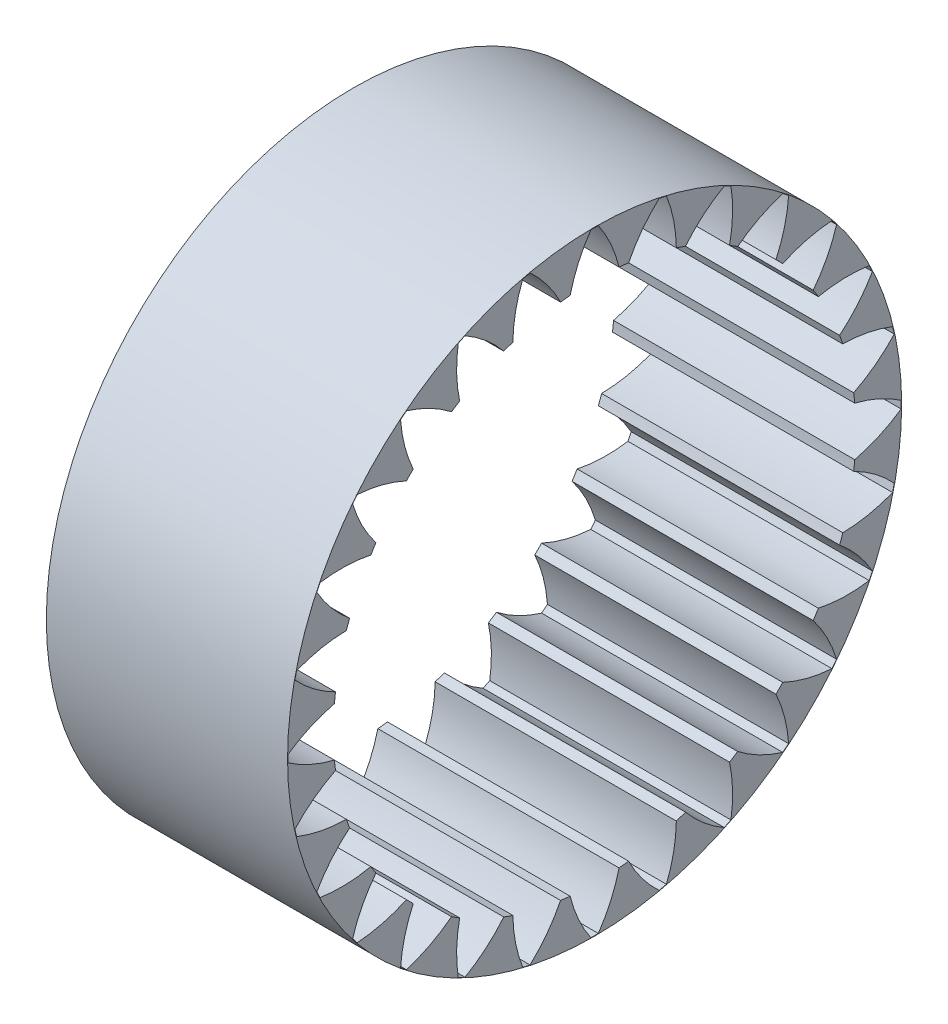
SolidWorks part; units mm, degrees
ref_plane "Plane1" through (0, 0, 0) normal (0, 0, 1) x (1, 0, 0)
ref_plane "Plane2" through (0, 0, 0) normal (0, 1, 0) x (1, 0, 0)
ref_plane "Plane3" through (0, 0, 0) normal (1, 0, 0) x (0, 0, -1)
sketch "HoldingSke" plane through (0, 0, 0) normal (0, 1, 0) x (1, 0, 0)
  line L0 (0, 0) -> (0.8829, -0.4695)
  line L1 (-15, 0) -> (100, 0) construction
  line L2 (0, 0) -> (-2.1039, 2.3779)
  line L3 (0, 0) -> (-11.863, 4.5341)
  line L4 (0, 0) -> (7.6251, 4.0544)
  line L5 (0, 0) -> (-23.7986, -8.8762)
  line L6 (0, 0) -> (-10.5278, -7.1032)
  line L7 (-2.1039, 2.3779) -> (3.3635, 27.1825)
  line L8 (-76.2, 3.3779) -> (-54.61, 3.3779)
  line L9 (-71.009, 38.7566) -> (-53.1078, 45.2721)
  line L10 (-76.2, 71.12) -> (104.1128, 71.12)
  line L11 (0, 0) -> (-12, 0)
  line L12 (-76.2, 101.6) -> (-76.162, 101.6)
  line L13 (24.9733, 27.94) -> (52.9518, 28.4284)
  line L14 (24.9733, 27.94) -> (24.9743, 27.94)
  line L15 (24.9733, 27.94) -> (100.4006, 29.5858)
  circle A0 centre (0, 0) radius 12.5
  circle A1 centre (0, 0) radius 12.7
  circle A2 centre (0, 0) radius 12.7
  dimension "MHD" = 25.4
  dimension "Hub_dia" = 25.4
  dimension "Diameter" = 25
  dimension "Num_teeth" = 28
  dimension "Pitch" = 1
  dimension "Overall_len" = 25.4
  dimension "Show_teeth" = 28
  dimension "Thickness" = 12.7
  dimension "OAL" = 25.4001
  dimension "T_dim" = 21.59
  dimension "Ap" = 20
  dimension "H" = 19.05
  dimension "Pitch_radius" = 180.3128
  dimension "Width" = 12
  dimension "Backlash" = 0.038
  dimension "Addendum_fac" = 1
  dimension "Dedendum_fac" = 1.25
  dimension "Clearance_fac" = 0.25
  dimension "Dedendum_add" = 0.001
  dimension "Module" = 1
sketch "BasProSke" plane through (0, 0, 0) normal (0, 1, 0) x (1, 0, 0)
  line L0 (-10, 0) -> (60, 0) construction
  line L1 (0, 13) -> (0, 15.2764)
  line L2 (0, 13) -> (12, 13)
  line L3 (12, 13) -> (12, 15.2764)
  line L4 (12, 15.2764) -> (0, 15.2764)
  dimension "Thickness" = 12
  dimension "Diameter" = 30.5528
  dimension "Inside_diameter" = 26
revolve "Base-Revolve" add sketch "BasProSke" angle 360 about L0
sketch "TooCutSke" plane through (0, 0, 0) normal (1, 0, 0) x (0, 0, -1)
  line L3 (0.88, 13.9723) -> (0.88, 53.6633) construction
  line L4 (0, 0) -> (0, 59.563) construction
  line L5 (0, 0) -> (-7.6503, 67.8979) construction
  line L6 (-5.584, 11.2859) -> (36.2792, 16.0027) construction
  circle A0 centre (0, 0) radius 14 construction
  circle A1 centre (0, 0) radius 15.251 construction
  circle A2 centre (0, 0) radius 11.8401 construction
  circle A3 centre (0, 0) radius 12.9746 construction
  arc A4 (1.2234, 12.9168) -> (0.1855, 15.2499) centre (-5.584, 11.2859) ccw
  arc A5 (1.2234, 12.9168) -> (-1.2234, 12.9168) centre (0, 0) ccw
  arc A6 (0.1855, 15.2499) -> (-0.1855, 15.2499) centre (0, 0) ccw
  arc A7 (-0.1855, 15.2499) -> (-1.2234, 12.9168) centre (5.584, 11.2859) ccw
  dimension "Pitch_dia" = 28
  dimension "Base_dia" = 23.6803
  dimension "Root_dia" = 30.502
  dimension "Overcut_dia" = 25.9492
  dimension "Flank_rad" = 7
  dimension "Half_ang" = 6.429
  dimension "Half_CT" = 0.88
extrude "ToothCut" cut sketch "TooCutSke" along normal through all
fillet "Breaks" [suppressed] radius 0.1
fillet "RootFillets" [suppressed] radius 0.251
pattern_circular "TeethCuts" count 28 every 12.857 about axis through (-10, 0, 0) along (1, 0, 0) of "RootFillets", "Breaks", "ToothCut"
equation "' \"Module@HoldingSke\" = 6.35"
equation "' \"Num_teeth@HoldingSke\" = 24"
equation "' \"Ap@HoldingSke\" =  14.5"
equation "' \"Ap@HoldingSke\" = 14.5"
equation "' \"Width@HoldingSke\" = 12"
equation "' \"Diameter@HoldingSke\" = 8 * 25.4"
equation "' \"Show_teeth@HoldingSke\" = 100"
equation "' \"Backlash@HoldingSke\" = 0.009 * 25.4"
equation "' \"Addendum_fac@HoldingSke\" = 1.0"
equation "' \"Dedendum_fac@HoldingSke\" = 1.25"
equation "' \"Dedendum_add@HoldingSke\" = 0.00005 * 25.4"
equation "' \"Clearance_fac@HoldingSke\" = 0.25"
equation "\"Pitch@HoldingSke\" = 1 / \"Module@HoldingSke\" "
equation "\"Overcut_dia@TooCutSke\" = (\"Num_teeth@HoldingSke\" - 2 * \"Addendum_fac@HoldingSke\") / \"Pitch@HoldingSke\" - 0.002 * 25.4"
equation "\"Pitch_dia@TooCutSke\" = \"Num_teeth@HoldingSke\" / \"Pitch@HoldingSke\""
equation "\"Base_dia@TooCutSke\" = \"Num_teeth@HoldingSke\" / \"Pitch@HoldingSke\" * cos((\"Ap@HoldingSke\"  * 3.14159265 / 180)) * 0.90"
equation "\"Root_dia@TooCutSke\" = \"Num_teeth@HoldingSke\"  / \"Pitch@HoldingSke\" + 2 *  \"Dedendum_fac@HoldingSke\"/ \"Pitch@HoldingSke\" + \"Dedendum_add@HoldingSke\" * 2"
equation "\"Half_ang@TooCutSke\" = 180 / \"Num_teeth@HoldingSke\""
equation "\"Half_CT@TooCutSke\" = \"Num_teeth@HoldingSke\" / \"Pitch@HoldingSke\" * sin((3.14159265 / 2 / \"Num_teeth@HoldingSke\")) / 2 + 10 * \"Backlash@HoldingSke\" / 4"
equation "\"Flank_rad@TooCutSke\" = \"Num_teeth@HoldingSke\" / \"Pitch@HoldingSke\" / 4"
equation "\"Radius@RootFillets\"= \"Clearance_fac@HoldingSke\" / \"Pitch@HoldingSke\" + \"Dedendum_add@HoldingSke\""
equation "\"Break_rad@Breaks\" = 0.02 / \"Pitch@HoldingSke\" * 5"
equation "\"Num_teeth@TeethCuts\" = int( \"Show_teeth@HoldingSke\" ) + 1"
equation "\"Num_teeth@TeethCuts\" = ((sgn( \"Num_teeth@TeethCuts\" - \"Num_teeth@HoldingSke\" )-1)*( \"Num_teeth@TeethCuts\" - \"Num_teeth@HoldingSke\" ))/-2+ \"Num_teeth@HoldingSke\""
equation "\"Num_teeth@TeethCuts\" = ((sgn( \"Num_teeth@TeethCuts\" - 2.0)+1)*( \"Num_teeth@TeethCuts\" - 2.0))/2 +2.0"
equation "\"Angle@TeethCuts\" = 360.0 / \"Num_teeth@HoldingSke\""
equation "\"Diameter@BasProSke\" = \"Num_teeth@HoldingSke\"  / \"Pitch@HoldingSke\" + 2 *  \"Dedendum_fac@HoldingSke\"/ \"Pitch@HoldingSke\" + \"Dedendum_add@HoldingSke\" * 2 + 0.002 * 25.4"
equation "\"Diameter@BasProSke\" = ((sgn( \"Diameter@BasProSke\"  - \"Diameter@HoldingSke\" )+1)*( \"Diameter@BasProSke\"  - \"Diameter@HoldingSke\" ))/2 + \"Diameter@HoldingSke\""
equation "\"Inside_diameter@BasProSke\" =  (\"Num_teeth@HoldingSke\" - 2 * \"Addendum_fac@HoldingSke\") / \"Pitch@HoldingSke\" "
equation "\"Thickness@BasProSke\"  = \"Width@HoldingSke\""
